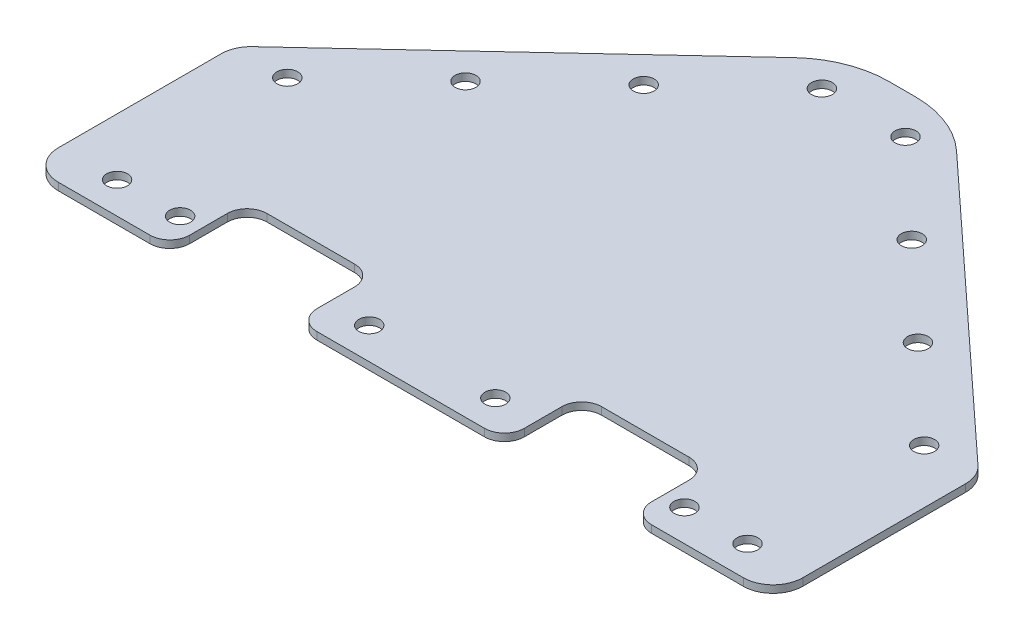
SolidWorks part; units mm, degrees
ref_plane "前视基准面" through (0, 0, 0) normal (0, 0, 1) x (1, 0, 0)
ref_plane "上视基准面" through (0, 0, 0) normal (0, 1, 0) x (1, 0, 0)
ref_plane "右视基准面" through (0, 0, 0) normal (1, 0, 0) x (0, 0, -1)
sketch "草图1" plane through (0, 0, 0) normal (0, 1, 0) x (1, 0, 0)
  line L0 (-30.5038, 56.6799) -> (-30.5038, -42.5743) construction
  line L1 (-100.3538, -35.3951) -> (99.6462, -35.3951) construction
  line L2 (-100.3538, -35.3951) -> (-100.3538, 66.0049) construction
  line L3 (-100.3538, 66.0049) -> (99.6462, 66.0049) construction
  line L4 (99.6462, -35.3951) -> (99.6462, 66.0049) construction
  line L5 (-105.5038, 6.0375) -> (-105.5038, -35.3951)
  line L6 (-105.5038, -35.3951) -> (44.4962, -35.3951)
  line L7 (44.4962, 6.0375) -> (44.4962, -35.3951)
  line L8 (-105.5038, 6.0375) -> (-47.0978, 60.4786)
  line L9 (-33.461, 65.8486) -> (-28.0445, 65.8486)
  line L10 (-14.4696, 60.5361) -> (44.4962, 6.0375)
  circle A0 centre (-94.0038, -29.0451) radius 2.0955
  arc A1 (-14.4696, 60.5361) -> (-28.0445, 65.8486) centre (-28.0445, 45.8486) ccw
  arc A2 (-33.461, 65.8486) -> (-47.0978, 60.4786) centre (-33.461, 45.8486) ccw
  circle A3 centre (32.9962, -29.0451) radius 2.0955
  circle A4 centre (-68.6038, -29.0451) radius 2.0955
  circle A5 centre (-43.2038, -29.0451) radius 2.0955
  circle A6 centre (-17.8038, -29.0451) radius 2.0955
  circle A7 centre (7.5962, -29.0451) radius 2.0955
extrude "凸台-拉伸1" add sketch "草图1" along normal blind 1.5
sketch "草图2" plane through (0, 1.5, 0) normal (0, 1, 0) x (1, 0, 0)
  line L0 (-94.0038, -29.0451) -> (-73.8233, -29.0451) construction
  line L1 (-47.0978, 60.4786) -> (-105.5038, 6.0375) construction
  line L2 (-94.655, 5.8969) -> (-27.3126, 68.6678) construction
  line L3 (-30.5038, -35.3951) -> (-30.5038, 89.1991) construction
  line L4 (-105.5038, -35.3951) -> (44.4962, -35.3951) construction
  circle A0 centre (-81.3038, -29.0451) radius 2.1
  circle A1 centre (20.2962, -29.0451) radius 2.1
  circle A2 centre (32.9962, -29.0451) radius 2.0955 construction
  circle A3 centre (-94.655, 5.8969) radius 2.1
  circle A4 centre (-76.0786, 23.2197) radius 2.1
  circle A5 centre (-57.5023, 40.5424) radius 2.1
  circle A6 centre (-38.9259, 57.8652) radius 2.1
  circle A7 centre (33.6474, 5.8969) radius 2.1
  circle A8 centre (15.071, 23.2197) radius 2.1
  circle A9 centre (-3.5054, 40.5424) radius 2.1
  circle A10 centre (-22.0818, 57.8652) radius 2.1
  dimension "D1" = 4.2
  dimension "D3" = 4.2
  dimension "D5" = 4.2
  dimension "D2" = 12.7
  dimension "D4" = 12.7
  dimension "D6" = 7.5
  dimension "D7" = 4
extrude "切除-拉伸1" cut sketch "草图2" against normal blind 1.5
fillet "圆角1" radius 6 4 edges at (44.4962, 0.75, -6.0375) (44.4962, 0.75, 35.3951) (-105.5038, 0.75, 35.3951) (-105.5038, 0.75, -6.0375)
sketch "草图3" plane through (0, 1.5, 0) normal (0, 1, 0) x (1, 0, 0)
  line L0 (-30.5038, -35.3951) -> (-30.5038, -20.1551)
  line L1 (-99.5038, -35.3951) -> (38.4962, -35.3951) construction
  line L2 (16.0178, -19.8223) -> (-9.622, -19.8223)
  line L7 (-77.0254, -35.3951) -> (-51.3857, -35.3951)
  line L8 (-77.0254, -35.3951) -> (-77.0254, -19.8223)
  line L9 (-77.0254, -19.8223) -> (-51.3857, -19.8223)
  line L10 (-51.3857, -35.3951) -> (-51.3857, -19.8223)
  line L11 (-9.622, -35.3951) -> (-9.622, -19.8223)
  line L12 (16.0178, -35.3951) -> (-9.622, -35.3951)
  line L13 (16.0178, -35.3951) -> (16.0178, -19.8223)
  point P4 (-30.5038, -27.7751)
  circle M13 centre (-68.6038, -29.0451) radius 2.0955
  line M25 (-99.5038, -35.3951) -> (38.4962, -35.3951)
  circle M29 centre (7.5962, -29.0451) radius 2.0955
  dimension "D1" = 15.24
extrude "切除-拉伸3" cut sketch "草图3" against normal blind 1.5 contours L10 L9 L8 M25 M13 | L13 L2 L11 M25 M29
fillet "圆角2" radius 4 8 edges at (-51.3857, 0.75, 19.8223) (-51.3857, 0.75, 35.3951) (-9.622, 0.75, 35.3951) (-9.622, 0.75, 19.8223) (16.0178, 0.75, 19.8223) (16.0178, 0.75, 35.3951) (-77.0254, 0.75, 35.3951) (-77.0254, 0.75, 19.8223)
